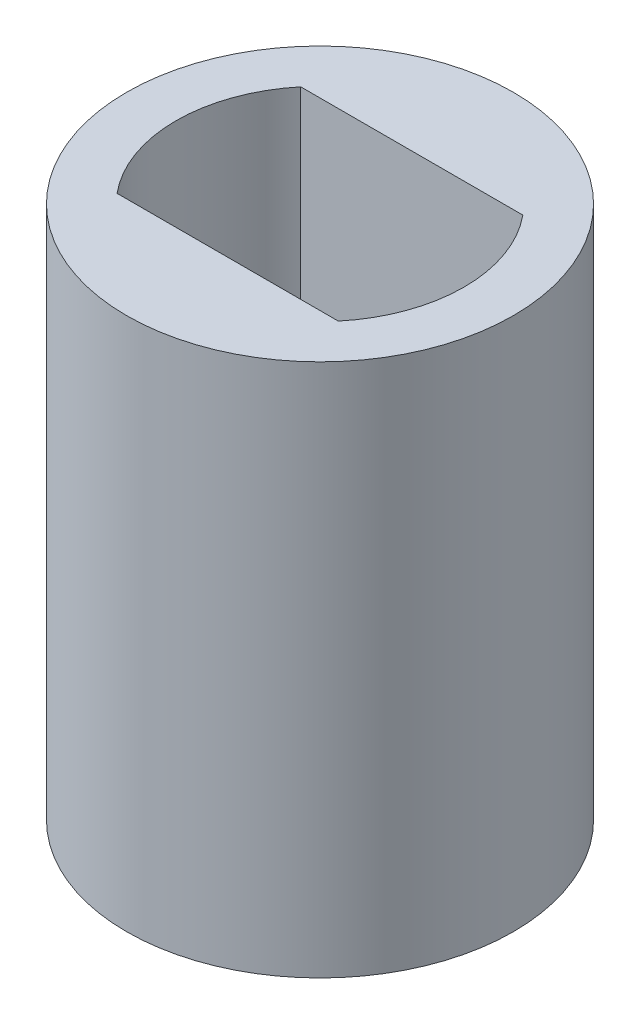
SolidWorks part; units mm, degrees
ref_plane "Plano frontal" through (0, 0, 0) normal (0, 0, 1) x (1, 0, 0)
ref_plane "Plano superior" through (0, 0, 0) normal (0, 1, 0) x (1, 0, 0)
ref_plane "Plano direito" through (0, 0, 0) normal (1, 0, 0) x (0, 0, -1)
sketch "Esboço1" plane through (0, 0, 0) normal (0, 1, 0) x (1, 0, 0)
  line L0 (0, 0) -> (-4.7758, 0) construction
  line L1 (-2.0812, 1.72) -> (2.0812, 1.72)
  line L3 (-2.073, -1.73) -> (2.073, -1.73)
  circle A0 centre (0, 0) radius 3.625
  arc A1 (-2.0812, 1.72) -> (-2.073, -1.73) centre (0, 0) ccw
  arc A2 (2.073, -1.73) -> (2.0812, 1.72) centre (0, 0) ccw
  dimension "D1" = 7.25
  dimension "D2" = 1.72
  dimension "D4" = 2.7
  dimension "D3" = 3.45
extrude "Ressalto-extrusão1" add sketch "Esboço1" along normal blind 10
